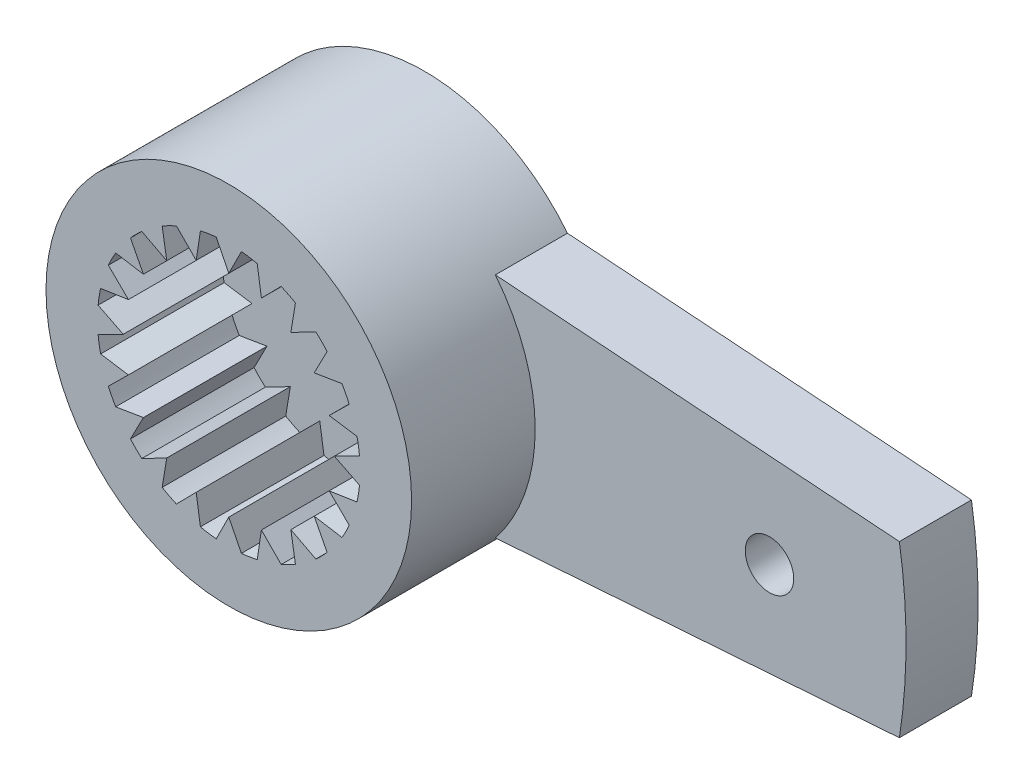
SolidWorks part; units mm, degrees
ref_plane "Front Plane" through (0, 0, 0) normal (0, 0, 1) x (1, 0, 0)
ref_plane "Top Plane" through (0, 0, 0) normal (0, 1, 0) x (1, 0, 0)
ref_plane "Right Plane" through (0, 0, 0) normal (1, 0, 0) x (0, 0, -1)
ref_plane "Plane4" through (0, 0, 0) normal (0, 0, 1) x (1, 0, 0)
ref_plane "Plane5" through (0, 0, -2.4) normal (0, 0, 1) x (1, 0, 0)
ref_plane "Plane6" through (0, 0, -3.8) normal (0, 0, 1) x (1, 0, 0)
sketch "Sketch5" plane through (0, 0, -2.4) normal (0, 0, 1) x (1, 0, 0)
  line L0 (2.7764, 2.2123) -> (10.6226, 1.65)
  line L1 (2.7764, -2.2123) -> (10.6226, -1.65)
  arc A0 (10.6226, 1.65) -> (10.6226, -1.65) centre (0.1655, 0) cw
  arc A1 (2.7764, 2.2123) -> (2.7764, -2.2123) centre (0, 0) cw
sketch "Sketch6" plane through (0, 0, -2.4) normal (0, 0, 1) x (1, 0, 0)
  circle A0 centre (8.1, 0) radius 0.4708
sketch "Sketch7" plane through (0, 0, 0) normal (0, 0, 1) x (1, 0, 0)
  line L0 (-0.2447, 2.5382) -> (0, 2.05)
  line L1 (0, 2.05) -> (0.2447, 2.5382)
  line L2 (0.5516, 2.4896) -> (0.6335, 1.9497)
  line L3 (0.6335, 1.9497) -> (1.0171, 2.3384)
  line L4 (1.294, 2.1973) -> (1.205, 1.6585)
  line L5 (1.205, 1.6585) -> (1.6899, 1.9096)
  line L6 (1.9096, 1.6899) -> (1.6585, 1.205)
  line L7 (1.6585, 1.205) -> (2.1973, 1.294)
  line L8 (2.3384, 1.0171) -> (1.9497, 0.6335)
  line L9 (1.9497, 0.6335) -> (2.4896, 0.5516)
  line L10 (2.5382, 0.2447) -> (2.05, 0)
  line L11 (2.05, 0) -> (2.5382, -0.2447)
  line L12 (2.4896, -0.5516) -> (1.9497, -0.6335)
  line L13 (1.9497, -0.6335) -> (2.3384, -1.0171)
  line L14 (2.1973, -1.294) -> (1.6585, -1.205)
  line L15 (1.6585, -1.205) -> (1.9096, -1.6899)
  line L16 (1.6899, -1.9096) -> (1.205, -1.6585)
  line L17 (1.205, -1.6585) -> (1.294, -2.1973)
  line L18 (1.0171, -2.3384) -> (0.6335, -1.9497)
  line L19 (0.6335, -1.9497) -> (0.5516, -2.4896)
  line L20 (0.2447, -2.5382) -> (0, -2.05)
  line L21 (0, -2.05) -> (-0.2447, -2.5382)
  line L22 (-0.5516, -2.4896) -> (-0.6335, -1.9497)
  line L23 (-0.6335, -1.9497) -> (-1.0171, -2.3384)
  line L24 (-1.294, -2.1973) -> (-1.205, -1.6585)
  line L25 (-1.205, -1.6585) -> (-1.6899, -1.9096)
  line L26 (-1.9096, -1.6899) -> (-1.6585, -1.205)
  line L27 (-1.6585, -1.205) -> (-2.1973, -1.294)
  line L28 (-2.3384, -1.0171) -> (-1.9497, -0.6335)
  line L29 (-1.9497, -0.6335) -> (-2.4896, -0.5516)
  line L30 (-2.5382, -0.2447) -> (-2.05, 0)
  line L31 (-2.05, 0) -> (-2.5382, 0.2447)
  line L32 (-2.4896, 0.5516) -> (-1.9497, 0.6335)
  line L33 (-1.9497, 0.6335) -> (-2.3384, 1.0171)
  line L34 (-2.1973, 1.294) -> (-1.6585, 1.205)
  line L35 (-1.6585, 1.205) -> (-1.9096, 1.6899)
  line L36 (-1.6899, 1.9096) -> (-1.205, 1.6585)
  line L37 (-1.205, 1.6585) -> (-1.294, 2.1973)
  line L38 (-1.0171, 2.3384) -> (-0.6335, 1.9497)
  line L39 (-0.6335, 1.9497) -> (-0.5516, 2.4896)
  arc A0 (-0.2447, 2.5382) -> (0.2447, 2.5382) centre (0, 0) cw
  circle A1 centre (0, 0) radius 2.55 construction
  arc A2 (0.5516, 2.4896) -> (1.0171, 2.3384) centre (0, 0) cw
  arc A3 (1.294, 2.1973) -> (1.6899, 1.9096) centre (0, 0) cw
  arc A4 (1.9096, 1.6899) -> (2.1973, 1.294) centre (0, 0) cw
  arc A5 (2.3384, 1.0171) -> (2.4896, 0.5516) centre (0, 0) cw
  arc A6 (2.5382, 0.2447) -> (2.5382, -0.2447) centre (0, 0) cw
  arc A7 (2.4896, -0.5516) -> (2.3384, -1.0171) centre (0, 0) cw
  arc A8 (2.1973, -1.294) -> (1.9096, -1.6899) centre (0, 0) cw
  arc A9 (1.6899, -1.9096) -> (1.294, -2.1973) centre (0, 0) cw
  arc A10 (1.0171, -2.3384) -> (0.5516, -2.4896) centre (0, 0) cw
  arc A11 (0.2447, -2.5382) -> (-0.2447, -2.5382) centre (0, 0) cw
  arc A12 (-0.5516, -2.4896) -> (-1.0171, -2.3384) centre (0, 0) cw
  arc A13 (-1.294, -2.1973) -> (-1.6899, -1.9096) centre (0, 0) cw
  arc A14 (-1.9096, -1.6899) -> (-2.1973, -1.294) centre (0, 0) cw
  arc A15 (-2.3384, -1.0171) -> (-2.4896, -0.5516) centre (0, 0) cw
  arc A16 (-2.5382, -0.2447) -> (-2.5382, 0.2447) centre (0, 0) cw
  arc A17 (-2.4896, 0.5516) -> (-2.3384, 1.0171) centre (0, 0) cw
  arc A18 (-2.1973, 1.294) -> (-1.9096, 1.6899) centre (0, 0) cw
  arc A19 (-1.6899, 1.9096) -> (-1.294, 2.1973) centre (0, 0) cw
  arc A20 (-1.0171, 2.3384) -> (-0.5516, 2.4896) centre (0, 0) cw
  point P66 (0, 0)
  dimension "D1" = 20
extrude "Boss-Extrude2" add sketch "Sketch5" against normal up to surface (1.4 mm away) separate body up to plane "Plane6"
extrude "Cut-Extrude1" cut sketch "Sketch6" against normal through all contours A0
sketch "Sketch8" plane through (0, 0, 0) normal (0, 0, 1) x (1, 0, 0)
  circle A0 centre (0, 0) radius 3.55
extrude "Boss-Extrude3" add sketch "Sketch8" against normal up to surface (3.8 mm away) up to plane "Plane6"
sketch "Sketch9" plane through (0, 0, 0) normal (0, 0, 1) x (1, 0, 0)
  circle A0 centre (0, 0) radius 2.55
extrude "Cut-Extrude2" cut sketch "Sketch9" against normal up to surface (2.4 mm away)
extrude "Boss-Extrude4" add sketch "Sketch7" against normal up to surface (2.4 mm away) up to face at (2.55, 0, -2.4)
sketch "Sketch10" plane through (0, 0, 0) normal (0, 0, 1) x (1, 0, 0)
  line L0 (0, 0) -> (0, 5.767)
